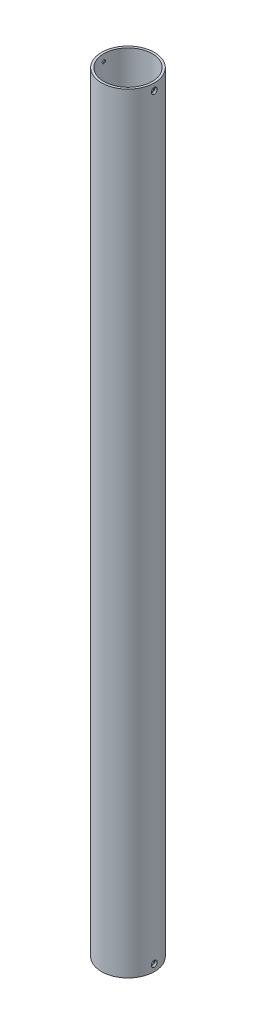
SolidWorks part; units mm, degrees
material "6061-T4 (SS)"
ref_plane "Front Plane" through (0, 0, 0) normal (0, 0, 1) x (1, 0, 0)
ref_plane "Top Plane" through (0, 0, 0) normal (0, 1, 0) x (1, 0, 0)
ref_plane "Right Plane" through (0, 0, 0) normal (1, 0, 0) x (0, 0, -1)
sketch "Sketch1" plane through (0, 0, 0) normal (0, 1, 0) x (1, 0, 0)
  circle A0 centre (0, 0) radius 19.05
  circle A1 centre (0, 0) radius 17.4244
  dimension "D1" = 38.1
  dimension "D2" = 1.6256
extrude "Boss-Extrude1" add sketch "Sketch1" along normal blind 555
sketch "Sketch38" plane through (0, 0, 0) normal (0, -1, 0) x (1, 0, 0)
  line L0 (0, 0) -> (19.05, 0)
  circle A0 centre (0, 0) radius 19.05 construction
ref_plane "Plane2" through (0, 0, 0) normal (0, 0, -1) x (1, 0, 0)
hole_wizard "CSK for M2 Countersunk Flat Head Screw10" positions "3DSketch18" profile "Sketch44" countersink size "M2" standard "DIN"
sketch3d "3DSketch18"
  line L0 (19.05, 0, 0) -> (19.05, 555, 0)
  line L1 (0, 0, 0) -> (19.05, 0, 0) construction
  circle A0 centre (0, 555, 0) radius 19.05 construction
  point P0 (19.05, 5, 0)
  point P8 (0, 574.05, 0)
  point P9 (19.05, 550, 0)
  dimension "D1" = 5
  dimension "D2" = 5
sketch "Sketch44" plane through (19.05, 5, 0) normal (0, 1, 0) x (0, 0, -1)
  line L0 (0, 0) -> (0, 10.721)
  line L1 (0, 10.721) -> (1.2, 10)
  line L2 (1.2, 10) -> (1.2, 1)
  line L3 (1.2, 1) -> (2.2, 0)
  line L5 (2.2, 0) -> (0, 0)
  line L6 (-1.2, 1) -> (-2.2, 0) construction
  line L10 (0, 10.721) -> (-1.2, 10) construction
  line L11 (0, -6.35) -> (0, 107.95) construction
  dimension "Hole Dia." = 2.4
  dimension "Hole Depth" = 10
  dimension "Near C'Sink Dia." = 4.4
  dimension "Near C'Sink Angle" = 90
  dimension "Drill Angle" = 118
pattern_circular "CirPattern2" count 2 over 360 about axis through (0, 555, 0) along (0, 1, 0) of "CSK for M2 Countersunk Flat Head Screw10"
